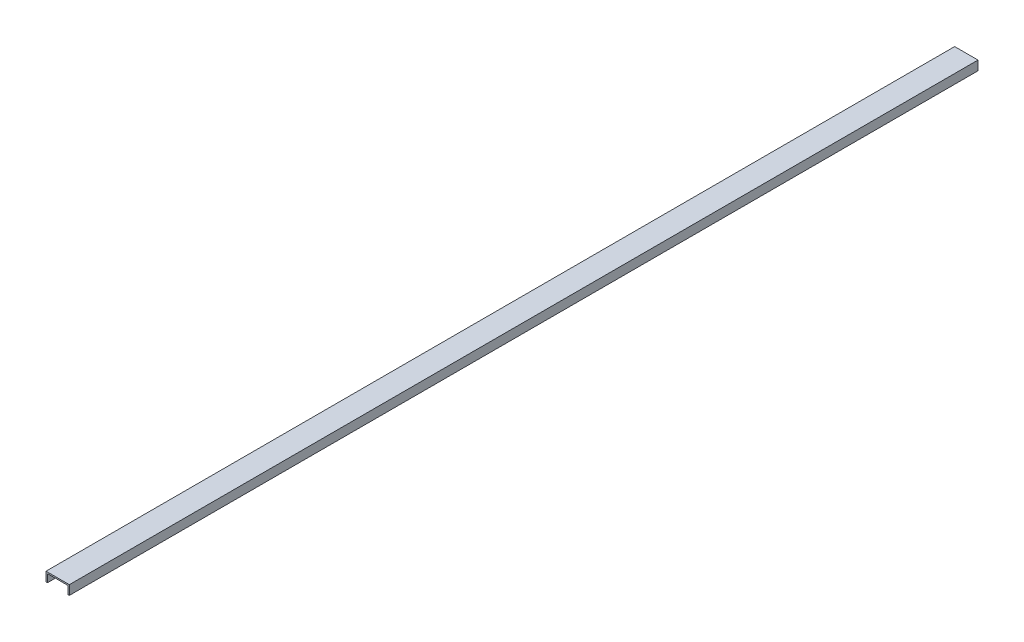
SolidWorks part; units mm, degrees
ref_plane "Front Plane" through (0, 0, 0) normal (0, 0, 1) x (1, 0, 0)
ref_plane "Top Plane" through (0, 0, 0) normal (0, 1, 0) x (1, 0, 0)
ref_plane "Right Plane" through (0, 0, 0) normal (1, 0, 0) x (0, 0, -1)
sketch "Sketch1" plane through (0, 0, 0) normal (0, 0, 1) x (1, 0, 0)
  line L0 (0, 0) -> (0, 20)
  line L1 (0, 20) -> (50, 20)
  line L2 (50, 20) -> (50, 0)
  line L3 (50, 0) -> (47, 0)
  line L4 (47, 0) -> (47, 17)
  line L5 (47, 17) -> (3, 17)
  line L6 (3, 17) -> (3, 0)
  line L7 (3, 0) -> (0, 0)
  dimension "D1" = 50
  dimension "D2" = 20
  dimension "D3" = 3
  dimension "D4" = 3
extrude "Boss-Extrude1" add sketch "Sketch1" along normal blind 1825
sketch "Sketch2" plane through (0, 0, 1825) normal (0, 0, 1) x (1, 0, 0)
  line L0 (0, 0) -> (0, 20)
  line L1 (0, 20) -> (50, 20)
  line L2 (50, 20) -> (50, 0)
  line L3 (50, 0) -> (47, 0)
  line L4 (47, 0) -> (47, 17)
  line L5 (47, 17) -> (3, 17)
  line L6 (3, 17) -> (3, 0)
  line L7 (3, 0) -> (0, 0)
extrude "Down" add sketch "Sketch2" along normal blind 47
sketch "Sketch3" plane through (0, 0, 0) normal (0, 0, -1) x (-1, 0, 0)
  line L0 (-50, 0) -> (-50, 20)
  line L1 (-50, 20) -> (0, 20)
  line L2 (0, 20) -> (0, 0)
  line L3 (0, 0) -> (-3, 0)
  line L4 (-3, 0) -> (-3, 17)
  line L5 (-3, 17) -> (-47, 17)
  line L6 (-47, 17) -> (-47, 0)
  line L7 (-47, 0) -> (-50, 0)
extrude "Up" add sketch "Sketch3" along normal blind 75
equation "\"boxWidth\"=1930.0"
equation "\"D1@Boss-Extrude1\"= \"indoorHeight\" + \"indoorHeight_para\" - 90 - 50"
equation "\"start\"=700.0"
equation "\"CarBeamWidth\"=700.0"
equation "\"WheelWidth\"=650.0"
equation "\"Wheel_FrontBoxDistance\"=1390.0"
equation "\"boxLength\"=5100.0"
equation "\"MetalSheet_3mm_length\"=5030.0"
equation "\"MetalSheet_3mm_width\"=1923.0"
equation "\"MetalSheet_3mm_FloorCut_L_length\"=1764.0"
equation "\"MetalSheet_3mm_FloorCut_L_disdance\"=1665.0"
equation "\"MetalSheet_3mm_FloorCut_R_length\"=1764.0"
equation "\"MetalSheet_3mm_FloorCut_R_disdance\"=1665.0"
equation "\"indoorHeight\"=1940.0"
equation "\"indoorHeight_para\"=25.0"
equation "\"rearLightHeight_para\"=265.0"
equation "\"doorColumnBar_A_FR_3mm_length_Cut\"=2310.0"
equation "\"A\"=0.0"
equation "\"haveDoor_R\"=1"
equation "\"side_door_bottom_R_3mm_length\"=1934.0"
equation "\"side_door_bottom_R_3mm_toFrontDistance\"=1583.0"
equation "\"1Bar_Side_RF_3mm_length\"=1493.0"
equation "\"1Bar_Side_RB_3mm_length\"=1493.0"
equation "\"DoorSeparator_RF_3mm_withHinge_toFrontDistance\"=1673.0"
equation "\"DoorSeparator_RF_3mm_withHinge_exist\"=1"
equation "\"DoorSeparator_RB_3mm_withHinge_toFrontDistance\"=3427.0"
equation "\"DoorSeparator_RB_3mm_withHinge_exist\"=1"
equation "\"Door_R1_L_open_Single_toFrontDistance\"=2547.5"
equation "\"Door_R1_L_open_Single_exist\"=1"
equation "\"door_base_long7_R1_L_open_Single_height\"=1890.0"
equation "\"door_base_short7_R1_L_open_Single_height\"=1890.0"
equation "\"door_base_short7_R1_L_open_Single_width\"=864"
equation "\"Door_R1_R_open_Single_toFrontDistance\"=3422.0"
equation "\"Door_R1_R_open_Single_exist\"=1"
equation "\"door_base_long7_R1_R_open_Single_height\"=1890.0"
equation "\"door_base_short7_R1_R_open_Single_height\"=1890.0"
equation "\"door_base_short7_R1_R_open_Single_width\"=864"
equation "\"x\"=66.0"
equation "\"door_base_double_BL_height\"=1890.0"
equation "\"door_base_short7_BL_Single_height\"=1890.0"
equation "\"door_base_short7_BL_Single_width\"=864"
equation "\"door_base_long7_BR_Single_height\"=1890.0"
equation "\"door_base_short7_BR_Single_height\"=1890.0"
equation "\"door_base_short7_BR_Single_width\"=864"
equation "\"da\"=62.0"
equation "\"SquareTube_length\"=1923.0"
equation "\"channelSteel_length\"=5030.0"
equation "\"SquareTube_inFront_AvgDistance\"=285.0"
equation "\"SquareTube_inFront_TotalCount\"=5"
equation "\"SquareTube_inFront1_cutDepth50_R\"=0.5"
equation "\"SquareTube_inFront1_cutDepth50_L\"=0.5"
equation "\"SquareTube_inFront2_cutDepth50_R\"=0.5"
equation "\"SquareTube_inFront2_cutDepth50_L\"=0.5"
equation "\"SquareTube_inFront3_cutDepth50_R\"=0.5"
equation "\"SquareTube_inFront3_cutDepth50_L\"=0.5"
equation "\"SquareTube_inFront4_cutDepth50_R\"=0.5"
equation "\"SquareTube_inFront4_cutDepth50_L\"=0.5"
equation "\"SquareTube_inFront5_cutDepth50_R\"=50"
equation "\"SquareTube_inFront5_cutDepth50_L\"=50"
equation "\"SquareTube_inFront6_cutDepth50_R\"=50"
equation "\"SquareTube_inFront6_cutDepth50_L\"=50"
equation "\"SquareTube_inFront7_cutDepth50_R\"=50"
equation "\"SquareTube_inFront7_cutDepth50_L\"=50"
equation "\"SquareTube_inFront8_cutDepth50_R\"=50"
equation "\"SquareTube_inFront8_cutDepth50_L\"=50"
equation "\"SquareTube_inFront9_cutDepth50_R\"=50"
equation "\"SquareTube_inFront9_cutDepth50_L\"=50"
equation "\"SquareTube_inFront10_cutDepth50_R\"=50"
equation "\"SquareTube_inFront10_cutDepth50_L\"=50"
equation "\"SquareTube_inFront11_cutDepth50_R\"=50"
equation "\"SquareTube_inFront11_cutDepth50_L\"=50"
equation "\"SquareTube_inFront12_cutDepth50_R\"=50"
equation "\"SquareTube_inFront12_cutDepth50_L\"=50"
equation "\"SquareTube_inFront13_cutDepth50_R\"=50"
equation "\"SquareTube_inFront13_cutDepth50_L\"=50"
equation "\"SquareTube_inFront14_cutDepth50_R\"=50"
equation "\"SquareTube_inFront14_cutDepth50_L\"=50"
equation "\"SquareTube_inBack_AvgDistance\"=333.125"
equation "\"SquareTube_inBack_TotalCount\"=9"
equation "\"SquareTube_inBack1_cutDepth50_R\"=50"
equation "\"SquareTube_inBack1_cutDepth50_L\"=50"
equation "\"SquareTube_inBack2_cutDepth50_R\"=50"
equation "\"SquareTube_inBack2_cutDepth50_L\"=50"
equation "\"SquareTube_inBack3_cutDepth50_R\"=50"
equation "\"SquareTube_inBack3_cutDepth50_L\"=50"
equation "\"SquareTube_inBack4_cutDepth50_R\"=50"
equation "\"SquareTube_inBack4_cutDepth50_L\"=50"
equation "\"SquareTube_inBack5_cutDepth50_R\"=50"
equation "\"SquareTube_inBack5_cutDepth50_L\"=50"
equation "\"SquareTube_inBack6_cutDepth50_R\"=0.5"
equation "\"SquareTube_inBack6_cutDepth50_L\"=0.5"
equation "\"SquareTube_inBack7_cutDepth50_R\"=0.5"
equation "\"SquareTube_inBack7_cutDepth50_L\"=0.5"
equation "\"SquareTube_inBack8_cutDepth50_R\"=0.5"
equation "\"SquareTube_inBack8_cutDepth50_L\"=0.5"
equation "\"doorColumnBar_A_FL_3mm_length_Cut\"=2310.0"
equation "\"B\"=0.0"
equation "\"haveDoor_L\"=1"
equation "\"side_door_bottom_L_3mm_length\"=1934.0"
equation "\"side_door_bottom_L_3mm_toFrontDistance\"=1583.0"
equation "\"1Bar_Side_LF_3mm_length\"=1493.0"
equation "\"1Bar_Side_LB_3mm_length\"=1493.0"
equation "\"DoorSeparator_LF_3mm_withHinge_toFrontDistance\"=1673.0"
equation "\"DoorSeparator_LF_3mm_withHinge_exist\"=1"
equation "\"DoorSeparator_LB_3mm_withHinge_toFrontDistance\"=3427.0"
equation "\"DoorSeparator_LB_3mm_withHinge_exist\"=1"
equation "\"Door_L1_L_open_Single_toFrontDistance\"=3422.0"
equation "\"Door_L1_L_open_Single_exist\"=1"
equation "\"door_base_long7_L1_L_open_Single_height\"=1890.0"
equation "\"door_base_short7_L1_L_open_Single_height\"=1890.0"
equation "\"door_base_short7_L1_L_open_Single_width\"=864"
equation "\"Door_L1_R_open_Single_toFrontDistance\"=2547.5"
equation "\"Door_L1_R_open_Single_exist\"=1"
equation "\"door_base_long7_L1_R_open_Single_height\"=1890.0"
equation "\"door_base_short7_L1_R_open_Single_height\"=1890.0"
equation "\"door_base_short7_L1_R_open_Single_width\"=864"
equation "\"D1@Down\" = IIF (  ( \"haveDoor_R\" )  = 1 , 60 , 70 ) "
equation "\"D1@Up\"= IIF ( ( \"haveDoor_L\" ) = 1 , 75 , 65 )"
